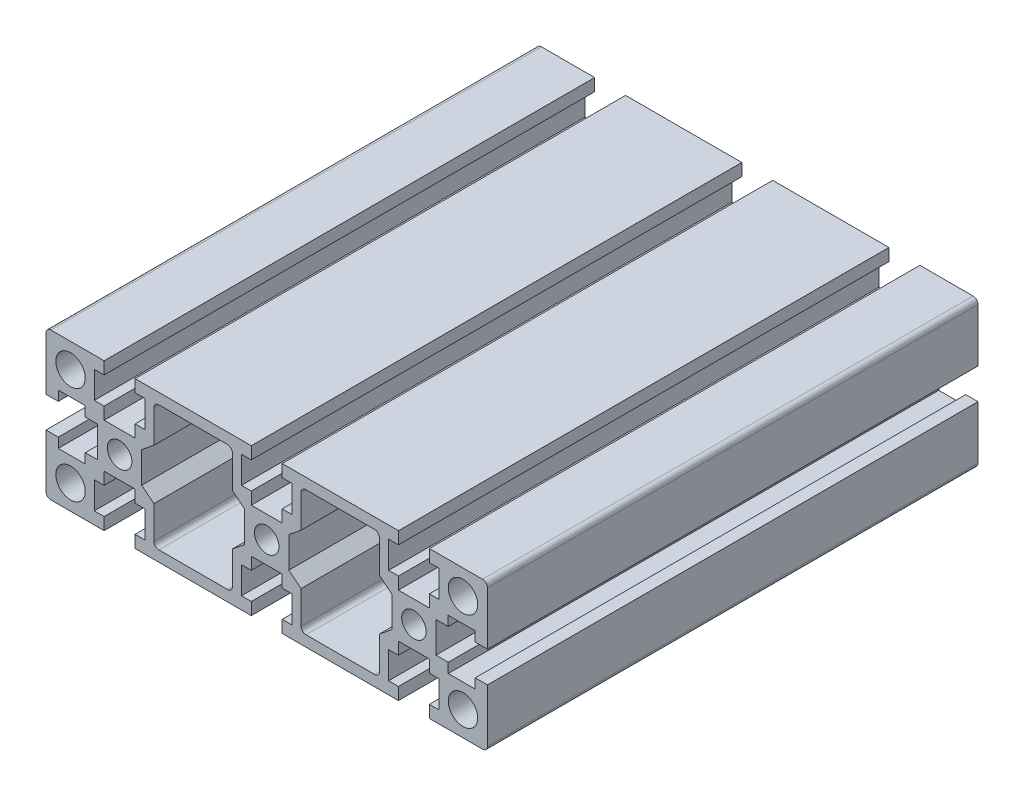
SolidWorks part; units mm, degrees
ref_plane "前视基准面" through (0, 0, 0) normal (0, 0, 1) x (1, 0, 0)
ref_plane "上视基准面" through (0, 0, 0) normal (0, 1, 0) x (1, 0, 0)
ref_plane "右视基准面" through (0, 0, 0) normal (1, 0, 0) x (0, 0, -1)
sketch "草图1" plane through (0, 0, 0) normal (0, 0, 1) x (1, 0, 0)
  line L0 (-25.8188, -14.8486) -> (-14.9688, -14.8486)
  line L1 (-25.8188, -12.3486) -> (-25.8188, -14.8486)
  line L2 (-23.8188, -12.3486) -> (-25.8188, -12.3486)
  line L3 (-24.4688, 0.1514) -> (-24.4688, 3.3014)
  line L4 (-23.8188, -6.8486) -> (-23.8188, -12.3486)
  line L5 (-25.8188, -6.8486) -> (-23.8188, -6.8486)
  line L6 (-25.8188, -4.3486) -> (-25.8188, -6.8486)
  line L7 (-28.9688, -4.3486) -> (-25.8188, -4.3486)
  line L8 (-32.1188, -4.3486) -> (-28.9688, -4.3486)
  line L9 (-32.1188, -6.8486) -> (-32.1188, -4.3486)
  line L10 (-34.1188, -6.8486) -> (-32.1188, -6.8486)
  line L11 (-34.1188, -12.3486) -> (-34.1188, -6.8486)
  line L12 (-13.9688, 12.9514) -> (-20.9688, 12.9514)
  line L13 (-32.1188, -12.3486) -> (-34.1188, -12.3486)
  line L14 (-25.8188, 15.1514) -> (-25.8188, 12.6514)
  line L15 (-32.1188, -14.8486) -> (-32.1188, -12.3486)
  line L16 (-25.8188, 12.6514) -> (-23.8188, 12.6514)
  line L17 (-42.9688, -14.8486) -> (-32.1188, -14.8486)
  line L18 (-23.8188, 12.6514) -> (-23.8188, 7.1514)
  line L19 (-23.8188, 7.1514) -> (-25.8188, 7.1514)
  line L20 (-43.9688, -2.9986) -> (-43.9688, -13.8486)
  line L21 (-25.8188, 7.1514) -> (-25.8188, 4.6514)
  line L22 (-41.4688, -2.9986) -> (-43.9688, -2.9986)
  line L23 (-25.8188, 4.6514) -> (-28.9688, 4.6514)
  line L24 (-41.4688, -4.9986) -> (-41.4688, -2.9986)
  line L25 (-28.9688, 4.6514) -> (-32.1188, 4.6514)
  line L26 (-35.9688, -4.9986) -> (-41.4688, -4.9986)
  line L27 (-32.1188, 4.6514) -> (-32.1188, 7.1514)
  line L28 (-35.9688, -2.9986) -> (-35.9688, -4.9986)
  line L29 (-32.1188, 7.1514) -> (-34.1188, 7.1514)
  line L30 (-33.4688, -2.9986) -> (-35.9688, -2.9986)
  line L31 (-34.1188, 7.1514) -> (-34.1188, 12.6514)
  line L32 (-33.4688, 0.1514) -> (-33.4688, -2.9986)
  line L33 (-34.1188, 12.6514) -> (-32.1188, 12.6514)
  line L34 (-33.4688, 3.3014) -> (-33.4688, 0.1514)
  line L35 (-32.1188, 12.6514) -> (-32.1188, 15.1514)
  line L36 (-35.9688, 3.3014) -> (-33.4688, 3.3014)
  line L37 (-32.1188, 15.1514) -> (-42.9688, 15.1514)
  line L38 (-35.9688, 5.3014) -> (-35.9688, 3.3014)
  line L39 (-41.4688, 5.3014) -> (-35.9688, 5.3014)
  line L40 (-43.9688, 14.1514) -> (-43.9688, 3.3014)
  line L41 (-41.4688, 3.3014) -> (-41.4688, 5.3014)
  line L42 (-43.9688, 3.3014) -> (-41.4688, 3.3014)
  line L43 (4.1812, -12.3486) -> (4.1812, -14.8486)
  line L44 (5.5312, -2.9986) -> (5.5312, 0.1514)
  line L45 (6.1812, -12.3486) -> (4.1812, -12.3486)
  line L46 (5.5312, 0.1514) -> (5.5312, 3.3014)
  line L47 (6.1812, -6.8486) -> (6.1812, -12.3486)
  line L48 (4.1812, -6.8486) -> (6.1812, -6.8486)
  line L49 (4.1812, -4.3486) -> (4.1812, -6.8486)
  line L50 (1.0312, -4.3486) -> (4.1812, -4.3486)
  line L51 (-2.1188, -4.3486) -> (1.0312, -4.3486)
  line L52 (-2.1188, -6.8486) -> (-2.1188, -4.3486)
  line L53 (-4.1188, -6.8486) -> (-2.1188, -6.8486)
  line L54 (-4.1188, -12.3486) -> (-4.1188, -6.8486)
  line L55 (-2.1188, -12.3486) -> (-4.1188, -12.3486)
  line L56 (4.1812, 15.1514) -> (4.1812, 12.6514)
  line L57 (-2.1188, -14.8486) -> (-2.1188, -12.3486)
  line L58 (4.1812, 12.6514) -> (6.1812, 12.6514)
  line L59 (-14.9688, -14.8486) -> (-2.1188, -14.8486)
  line L60 (6.1812, 12.6514) -> (6.1812, 7.1514)
  line L61 (6.1812, 7.1514) -> (4.1812, 7.1514)
  line L62 (4.1812, 7.1514) -> (4.1812, 4.6514)
  line L63 (4.1812, 4.6514) -> (1.0312, 4.6514)
  line L64 (1.0312, 4.6514) -> (-2.1188, 4.6514)
  line L65 (-2.1188, 4.6514) -> (-2.1188, 7.1514)
  line L66 (-2.1188, 7.1514) -> (-4.1188, 7.1514)
  line L67 (-4.1188, 7.1514) -> (-4.1188, 12.6514)
  line L68 (-4.1188, 12.6514) -> (-2.1188, 12.6514)
  line L69 (-2.1188, 12.6514) -> (-2.1188, 15.1514)
  line L70 (-24.4688, 3.3014) -> (-21.9688, 5.3014)
  line L71 (-21.9688, 5.3014) -> (-21.9688, 11.9514)
  line L72 (-25.8188, 15.1514) -> (-2.1188, 15.1514)
  line L73 (-3.4688, 0.1514) -> (-3.4688, 3.3014)
  line L74 (-13.9688, 12.9514) -> (-6.9688, 12.9514)
  line L75 (-3.4688, 3.3014) -> (-5.9688, 5.3014)
  line L76 (-5.9688, 5.3014) -> (-5.9688, 11.9514)
  line L77 (-24.4688, 0.1514) -> (-24.4688, -2.9986)
  line L78 (-13.9688, -12.6486) -> (-20.9688, -12.6486)
  line L79 (-24.4688, -2.9986) -> (-21.9688, -4.9986)
  line L80 (-21.9688, -4.9986) -> (-21.9688, -11.6486)
  line L81 (-3.4688, 0.1514) -> (-3.4688, -2.9986)
  line L82 (-13.9688, -12.6486) -> (-6.9688, -12.6486)
  line L83 (-3.4688, -2.9986) -> (-5.9688, -4.9986)
  line L84 (-5.9688, -4.9986) -> (-5.9688, -11.6486)
  line L85 (27.8812, -14.8486) -> (17.0312, -14.8486)
  line L86 (27.8812, -12.3486) -> (27.8812, -14.8486)
  line L87 (25.8812, -12.3486) -> (27.8812, -12.3486)
  line L88 (26.5312, 0.1514) -> (26.5312, 3.3014)
  line L89 (25.8812, -6.8486) -> (25.8812, -12.3486)
  line L90 (27.8812, -6.8486) -> (25.8812, -6.8486)
  line L91 (27.8812, -4.3486) -> (27.8812, -6.8486)
  line L92 (31.0312, -4.3486) -> (27.8812, -4.3486)
  line L93 (34.1812, -4.3486) -> (31.0312, -4.3486)
  line L94 (34.1812, -6.8486) -> (34.1812, -4.3486)
  line L95 (36.1812, -6.8486) -> (34.1812, -6.8486)
  line L96 (36.1812, -12.3486) -> (36.1812, -6.8486)
  line L97 (16.0312, 12.9514) -> (23.0312, 12.9514)
  line L98 (34.1812, -12.3486) -> (36.1812, -12.3486)
  line L99 (27.8812, 15.1514) -> (27.8812, 12.6514)
  line L100 (34.1812, -14.8486) -> (34.1812, -12.3486)
  line L101 (27.8812, 12.6514) -> (25.8812, 12.6514)
  line L102 (45.0312, -14.8486) -> (34.1812, -14.8486)
  line L103 (25.8812, 12.6514) -> (25.8812, 7.1514)
  line L104 (25.8812, 7.1514) -> (27.8812, 7.1514)
  line L105 (46.0312, -2.9986) -> (46.0312, -13.8486)
  line L106 (27.8812, 7.1514) -> (27.8812, 4.6514)
  line L107 (43.5312, -2.9986) -> (46.0312, -2.9986)
  line L108 (27.8812, 4.6514) -> (31.0312, 4.6514)
  line L109 (43.5312, -4.9986) -> (43.5312, -2.9986)
  line L110 (31.0312, 4.6514) -> (34.1812, 4.6514)
  line L111 (38.0312, -4.9986) -> (43.5312, -4.9986)
  line L112 (34.1812, 4.6514) -> (34.1812, 7.1514)
  line L113 (38.0312, -2.9986) -> (38.0312, -4.9986)
  line L114 (34.1812, 7.1514) -> (36.1812, 7.1514)
  line L115 (35.5312, -2.9986) -> (38.0312, -2.9986)
  line L116 (36.1812, 7.1514) -> (36.1812, 12.6514)
  line L117 (35.5312, 0.1514) -> (35.5312, -2.9986)
  line L118 (36.1812, 12.6514) -> (34.1812, 12.6514)
  line L119 (35.5312, 3.3014) -> (35.5312, 0.1514)
  line L120 (34.1812, 12.6514) -> (34.1812, 15.1514)
  line L121 (38.0312, 3.3014) -> (35.5312, 3.3014)
  line L122 (34.1812, 15.1514) -> (45.0312, 15.1514)
  line L123 (38.0312, 5.3014) -> (38.0312, 3.3014)
  line L124 (43.5312, 5.3014) -> (38.0312, 5.3014)
  line L125 (46.0312, 14.1514) -> (46.0312, 3.3014)
  line L126 (43.5312, 3.3014) -> (43.5312, 5.3014)
  line L127 (46.0312, 3.3014) -> (43.5312, 3.3014)
  line L128 (17.0312, -14.8486) -> (4.1812, -14.8486)
  line L129 (26.5312, 3.3014) -> (24.0312, 5.3014)
  line L130 (24.0312, 5.3014) -> (24.0312, 11.9514)
  line L131 (27.8812, 15.1514) -> (4.1812, 15.1514)
  line L132 (16.0312, 12.9514) -> (9.0312, 12.9514)
  line L133 (5.5312, 3.3014) -> (8.0312, 5.3014)
  line L134 (8.0312, 5.3014) -> (8.0312, 11.9514)
  line L135 (26.5312, 0.1514) -> (26.5312, -2.9986)
  line L136 (16.0312, -12.6486) -> (23.0312, -12.6486)
  line L137 (26.5312, -2.9986) -> (24.0312, -4.9986)
  line L138 (24.0312, -4.9986) -> (24.0312, -11.6486)
  line L139 (16.0312, -12.6486) -> (9.0312, -12.6486)
  line L140 (5.5312, -2.9986) -> (8.0312, -4.9986)
  line L141 (8.0312, -4.9986) -> (8.0312, -11.6486)
  arc A0 (-35.9688, 10.1514) -> (-41.9688, 10.1514) centre (-38.9688, 10.1514) ccw
  arc A1 (-41.9688, 10.1514) -> (-35.9688, 10.1514) centre (-38.9688, 10.1514) ccw
  arc A2 (-41.9688, -9.8486) -> (-35.9688, -9.8486) centre (-38.9688, -9.8486) ccw
  arc A3 (-35.9688, -9.8486) -> (-41.9688, -9.8486) centre (-38.9688, -9.8486) ccw
  arc A4 (-26.4688, 0.1514) -> (-31.4688, 0.1514) centre (-28.9688, 0.1514) ccw
  arc A5 (-31.4688, 0.1514) -> (-26.4688, 0.1514) centre (-28.9688, 0.1514) ccw
  arc A6 (-20.9688, 12.9514) -> (-21.9688, 11.9514) centre (-20.9688, 11.9514) ccw
  arc A7 (-43.9688, -13.8486) -> (-42.9688, -14.8486) centre (-42.9688, -13.8486) ccw
  arc A8 (-42.9688, 15.1514) -> (-43.9688, 14.1514) centre (-42.9688, 14.1514) ccw
  arc A9 (3.5312, 0.1514) -> (-1.4688, 0.1514) centre (1.0312, 0.1514) ccw
  arc A10 (-1.4688, 0.1514) -> (3.5312, 0.1514) centre (1.0312, 0.1514) ccw
  arc A11 (-5.9688, 11.9514) -> (-6.9688, 12.9514) centre (-6.9688, 11.9514) ccw
  arc A12 (-21.9688, -11.6486) -> (-20.9688, -12.6486) centre (-20.9688, -11.6486) ccw
  arc A13 (-6.9688, -12.6486) -> (-5.9688, -11.6486) centre (-6.9688, -11.6486) ccw
  arc A14 (44.0312, 10.1514) -> (38.0312, 10.1514) centre (41.0312, 10.1514) ccw
  arc A15 (38.0312, 10.1514) -> (44.0312, 10.1514) centre (41.0312, 10.1514) ccw
  arc A16 (38.0312, -9.8486) -> (44.0312, -9.8486) centre (41.0312, -9.8486) ccw
  arc A17 (44.0312, -9.8486) -> (38.0312, -9.8486) centre (41.0312, -9.8486) ccw
  arc A18 (33.5312, 0.1514) -> (28.5312, 0.1514) centre (31.0312, 0.1514) ccw
  arc A19 (28.5312, 0.1514) -> (33.5312, 0.1514) centre (31.0312, 0.1514) ccw
  arc A20 (24.0312, 11.9514) -> (23.0312, 12.9514) centre (23.0312, 11.9514) ccw
  arc A21 (45.0312, -14.8486) -> (46.0312, -13.8486) centre (45.0312, -13.8486) ccw
  arc A22 (46.0312, 14.1514) -> (45.0312, 15.1514) centre (45.0312, 14.1514) ccw
  arc A23 (9.0312, 12.9514) -> (8.0312, 11.9514) centre (9.0312, 11.9514) ccw
  arc A24 (23.0312, -12.6486) -> (24.0312, -11.6486) centre (23.0312, -11.6486) ccw
  arc A25 (8.0312, -11.6486) -> (9.0312, -12.6486) centre (9.0312, -11.6486) ccw
extrude "凸台-拉伸1" add sketch "草图1" along normal blind 100
